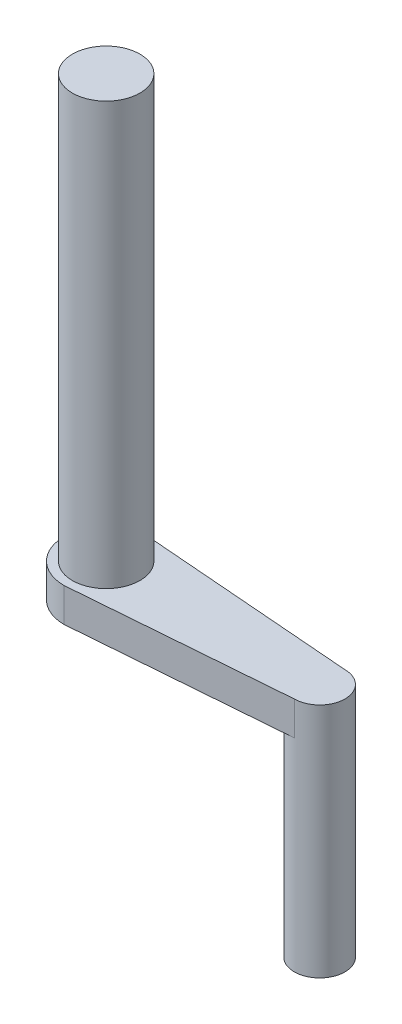
SolidWorks part; units mm, degrees
ref_plane "Front Plane" through (0, 0, 0) normal (0, 0, 1) x (1, 0, 0)
ref_plane "Top Plane" through (0, 0, 0) normal (0, 1, 0) x (1, 0, 0)
ref_plane "Right Plane" through (0, 0, 0) normal (1, 0, 0) x (0, 0, -1)
sketch "Sketch1" plane through (0, 0, 0) normal (0, 1, 0) x (1, 0, 0)
  line L0 (-80.7708, 27.2954) -> (-67.2845, 27.2954) construction
  line L1 (-80.7708, 29.7954) -> (-68.1295, 28.7954)
  line L2 (-80.7708, 24.7954) -> (-68.1295, 25.7954)
  arc A0 (-80.7708, 29.7954) -> (-80.7708, 24.7954) centre (-80.7708, 27.2954) ccw
  arc A1 (-68.1295, 25.7954) -> (-68.1295, 28.7954) centre (-68.1295, 27.2954) ccw
extrude "Boss-Extrude5" add sketch "Sketch1" along normal blind 2
sketch "Sketch5" plane through (0, 2, 0) normal (0, 1, 0) x (1, 0, 0)
  circle A0 centre (-80.7708, 27.2954) radius 2
  arc A1 (-80.7708, 29.7954) -> (-80.7708, 24.7954) centre (-80.7708, 27.2954) ccw construction
  dimension "D1" = 0
extrude "Boss-Extrude6" add sketch "Sketch5" along normal blind 25
sketch "Sketch6" plane through (0, 0, 0) normal (0, -1, 0) x (1, 0, 0)
  circle A0 centre (-68.1295, -27.2954) radius 1.5
extrude "Boss-Extrude7" add sketch "Sketch6" along normal blind 12
